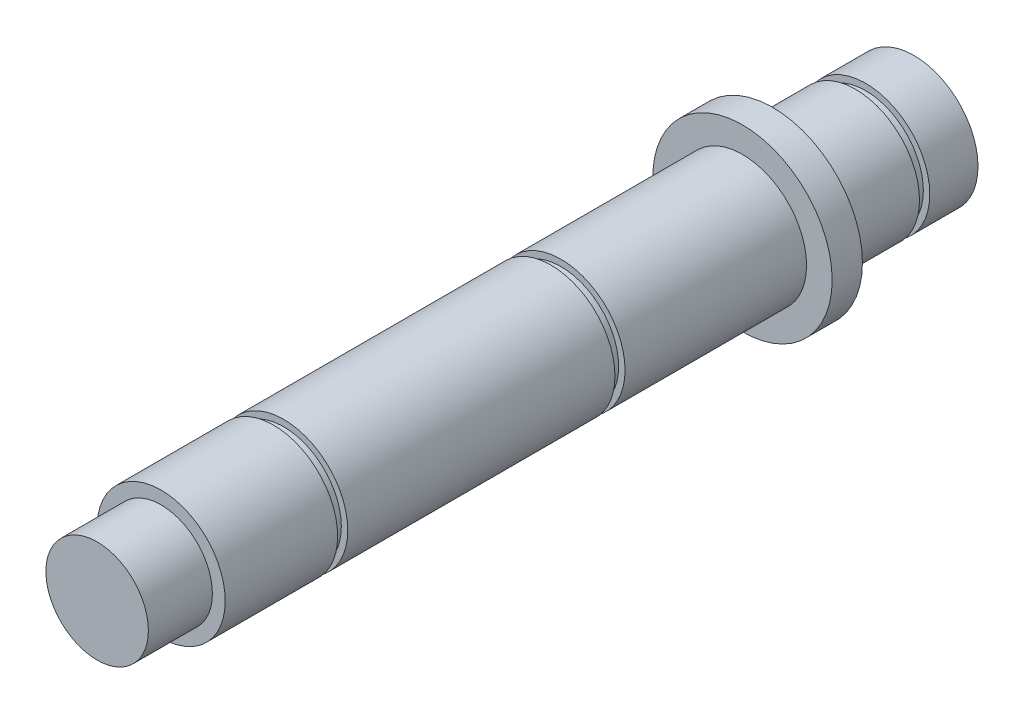
SolidWorks part; units mm, degrees
ref_plane "Front Plane" through (0, 0, 0) normal (0, 0, 1) x (1, 0, 0)
ref_plane "Top Plane" through (0, 0, 0) normal (0, 1, 0) x (1, 0, 0)
ref_plane "Right Plane" through (0, 0, 0) normal (1, 0, 0) x (0, 0, -1)
sketch "Sketch1" plane through (0, 0, 0) normal (0, 0, 1) x (1, 0, 0)
  circle A0 centre (0, 0) radius 6.35
  dimension "D1" = 12.7
extrude "Boss-Extrude1" add sketch "Sketch1" against normal blind 81
sketch "Sketch2" plane through (0, 0, 0) normal (0, 0, 1) x (1, 0, 0)
  circle A0 centre (0, 0) radius 5.715
  circle A1 centre (0.049, 0) radius 12.7
  dimension "D1" = 11.43
  dimension "D2" = 25.4
extrude "Cut-Extrude1" cut sketch "Sketch2" against normal blind 1.016 from offset 75.2 offset against normal yes
sketch "Sketch3" plane through (0, 0, 0) normal (0, 0, 1) x (1, 0, 0)
  circle A0 centre (0, 0) radius 8.89
  dimension "D1" = 17.78
extrude "Boss-Extrude2" add sketch "Sketch3" along normal blind 3 from offset 67 offset against normal yes
sketch "Sketch4" plane through (0, 0, 0) normal (0, 0, 1) x (1, 0, 0)
  circle A0 centre (0, 0) radius 5.08
  circle A1 centre (0, 0) radius 7.62
  dimension "D1" = 10.16
  dimension "D2" = 15.24
extrude "Cut-Extrude2" cut sketch "Sketch4" against normal blind 6.35
sketch "Sketch5" plane through (0, 0, 0) normal (0, 0, 1) x (1, 0, 0)
  circle A0 centre (0, 0) radius 5.715
  circle A1 centre (0, 0) radius 12.7
  dimension "D1" = 11.43
  dimension "D2" = 25.4
extrude "Cut-Extrude4" cut sketch "Sketch5" against normal blind 1 from offset 17.5 offset against normal yes
sketch "Sketch6" plane through (0, 0, 0) normal (0, 0, 1) x (1, 0, 0)
  circle A0 centre (0, 0) radius 5.715
  circle A1 centre (0, 0) radius 12.7
  dimension "D1" = 11.43
  dimension "D2" = 25.4
extrude "Cut-Extrude5" cut sketch "Sketch6" against normal blind 1 from offset 45
